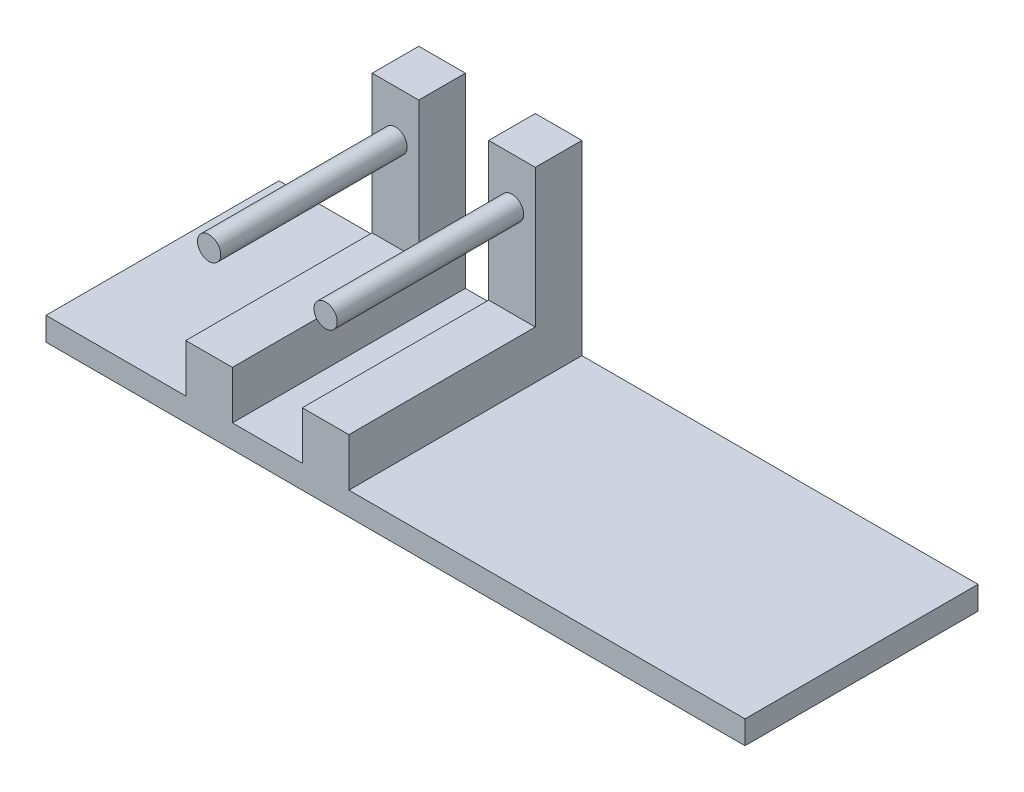
SolidWorks part; units mm, degrees
ref_plane "Front Plane" through (0, 0, 0) normal (0, 0, 1) x (1, 0, 0)
ref_plane "Top Plane" through (0, 0, 0) normal (0, 1, 0) x (1, 0, 0)
ref_plane "Right Plane" through (0, 0, 0) normal (1, 0, 0) x (0, 0, -1)
sketch "Sketch1" plane through (0, 0, 0) normal (0, 0, 1) x (1, 0, 0)
  line L0 (0, 5) -> (30, 5)
  line L1 (0, 0) -> (150, 0)
  line L2 (0, 0) -> (0, 5)
  line L4 (150, 0) -> (150, 5)
  line L5 (30, 5) -> (30, 45)
  line L6 (30, 45) -> (40, 45)
  line L7 (40, 45) -> (40, 5)
  line L8 (40, 5) -> (55, 5)
  line L9 (55, 5) -> (55, 45)
  line L10 (55, 45) -> (65, 45)
  line L11 (65, 45) -> (65, 5)
  line L12 (65, 5) -> (150, 5)
  point P1 (117.1276, 45)
  point P2 (47.7251, 45)
  point P7 (70.2153, 45)
  dimension "D1" = 150
  dimension "D2" = 10
  dimension "D3" = 10
  dimension "D4" = 40
  dimension "D5" = 5
  dimension "D6" = 15
  dimension "D7" = 30
extrude "Boss-Extrude1" add sketch "Sketch1" along normal blind 50
sketch "Sketch2" plane through (0, 0, 50) normal (0, 0, 1) x (1, 0, 0)
  line L0 (55, 45) -> (55, 5) construction
  line L1 (65, 45) -> (55, 45) construction
  line L2 (65, 5) -> (65, 45) construction
  line L3 (30, 45) -> (65, 45)
  line L4 (30, 45) -> (30, 15.3178)
  line L5 (30, 15.3178) -> (65, 15.3178)
  line L6 (65, 45) -> (65, 15.3178)
  circle A0 centre (35, 35) radius 2.5
  circle A1 centre (60, 35) radius 2.5
  dimension "D1" = 25
  dimension "D2" = 5
  dimension "D3" = 5
  dimension "D4" = 10
extrude "Cut-Extrude1" cut sketch "Sketch2" against normal blind 40
